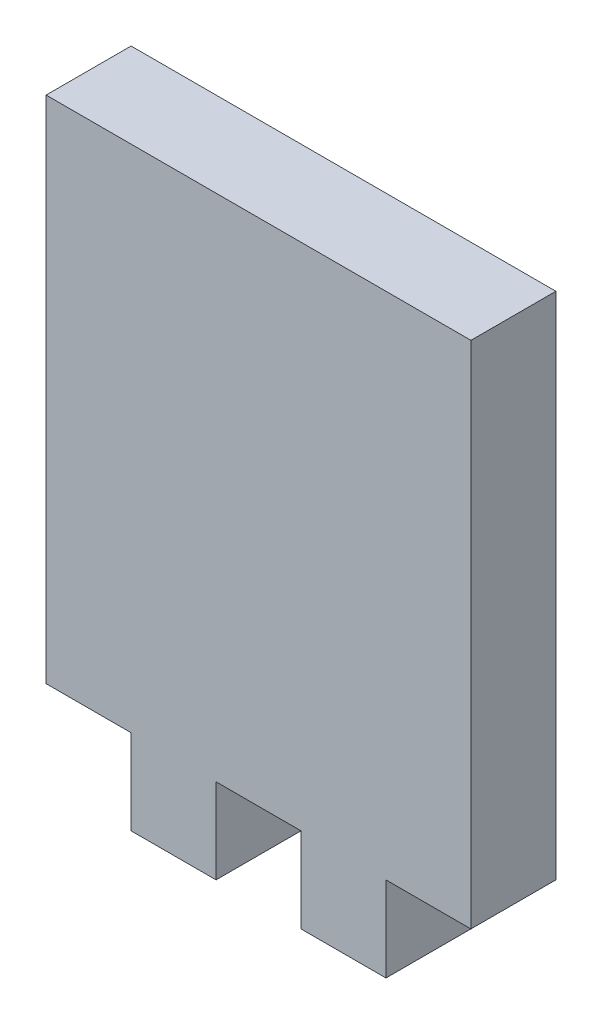
SolidWorks part; units mm, degrees
ref_plane "Plan de face" through (0, 0, 0) normal (0, 0, 1) x (1, 0, 0)
ref_plane "Plan de dessus" through (0, 0, 0) normal (0, 1, 0) x (1, 0, 0)
ref_plane "Plan de droite" through (0, 0, 0) normal (1, 0, 0) x (0, 0, -1)
sketch "Esquisse1" plane through (0, 0, 0) normal (0, 0, 1) x (1, 0, 0)
  line L0 (-50.0134, 4.11) -> (-45.0134, 4.11)
  line L1 (-45.0134, 4.11) -> (-45.0134, -0.89)
  line L2 (-45.0134, -0.89) -> (-40.0134, -0.89)
  line L3 (-40.0134, -0.89) -> (-40.0134, 4.11)
  line L4 (-40.0134, 4.11) -> (-35.0134, 4.11)
  line L5 (-35.0134, 4.11) -> (-35.0134, -0.89)
  line L7 (-50.0134, 4.11) -> (-50.0134, 34.11)
  line L8 (-50.0134, 34.11) -> (-25.0134, 34.11)
  line L9 (-35.0134, -0.89) -> (-30.0134, -0.89)
  line L10 (-30.0134, -0.89) -> (-30.0134, 4.11)
  line L11 (-30.0134, 4.11) -> (-25.0134, 4.11)
  line L14 (-25.0134, 4.11) -> (-25.0134, 34.11)
  dimension "D1" = 30
  dimension "D2" = 5
  dimension "D3" = 5
  dimension "D4" = 90
extrude "Boss.-Extru.1" add sketch "Esquisse1" along normal blind 5
